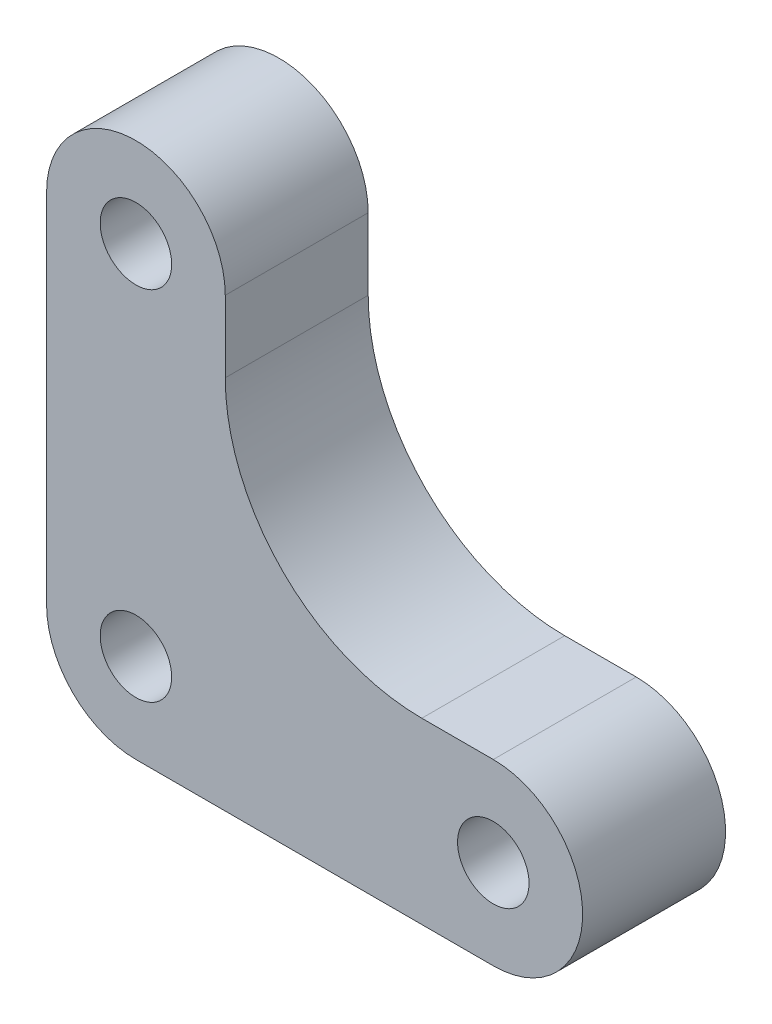
SolidWorks part; units mm, degrees
ref_plane "Front Plane" through (0, 0, 0) normal (0, 0, 1) x (1, 0, 0)
ref_plane "Top Plane" through (0, 0, 0) normal (0, 1, 0) x (1, 0, 0)
ref_plane "Right Plane" through (0, 0, 0) normal (1, 0, 0) x (0, 0, -1)
ref_plane "Plane1" through (0, 0, -13) normal (0, 0, -1) x (-1, 0, 0)
sketch "Sketch1" plane through (0, 0, -13) normal (0, 0, -1) x (-1, 0, 0)
  line L0 (15, 20) -> (15, 5)
  line L1 (15, 5) -> (0, 5)
  line L2 (0, -5) -> (25, -5)
  line L3 (25, -5) -> (25, 20)
  arc A0 (0, 5) -> (0, -5) centre (0, 0) ccw
  arc A1 (25, 20) -> (15, 20) centre (20, 20) ccw
extrude "Boss-Extrude1" add sketch "Sketch1" against normal blind 8
sketch "Sketch2" plane through (0, 0, -13) normal (0, 0, -1) x (-1, 0, 0)
  line L0 (0, -3) -> (23, -3)
  line L1 (23, -3) -> (23, 20)
  line L2 (17, 20) -> (17, 3)
  line L3 (17, 3) -> (0, 3)
  arc A0 (0, 3) -> (0, -3) centre (0, 0) ccw
  arc A1 (23, 20) -> (17, 20) centre (20, 20) ccw
extrude "Cut-Extrude1" cut sketch "Sketch2" against normal blind 3
hole_wizard "Ø4.0 (4) Diameter Hole1" positions "Sketch4" profile "Sketch3" hole size "Ø4.0" standard "ANSI Metric"
sketch "Sketch4" plane through (0, 0, -5) normal (0, 0, 1) x (1, 0, 0)
  point P0 (-20, 0)
  point P1 (-20, 20)
  point P2 (0, 0)
sketch "Sketch3" plane through (-20, 0, -5) normal (1, 0, 0) x (0, -1, 0)
  line L0 (0, 0) -> (0, 8)
  line L1 (0, 8) -> (2, 8)
  line L2 (2, 8) -> (2, 0)
  line L5 (2, 0) -> (0, 0)
  line L11 (0, -6.35) -> (0, 107.95) construction
  dimension "Thru Hole Dia." = 4
  dimension "Thru Hole Depth" = 8
fillet "Fillet1" radius 3 1 edges at (-23, -3, -11.5)
fillet "Fillet2" radius 5 1 edges at (-25, -5, -9)
fillet "Fillet3" radius 11 1 edges at (-15, 5, -9)
fillet "Fillet4" radius 13 1 edges at (-17, 3, -11.5)
